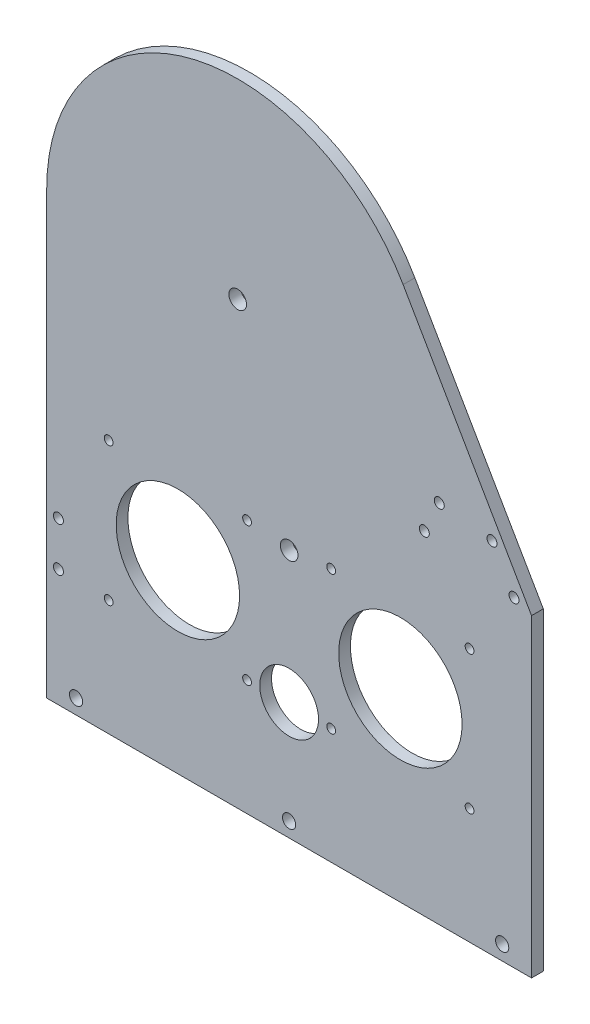
SolidWorks part; units mm, degrees
ref_plane "Plan1" through (0, 0, 0) normal (0, 0, 1) x (1, 0, 0)
ref_plane "Plan2" through (0, 0, 0) normal (0, 1, 0) x (1, 0, 0)
ref_plane "Plan3" through (0, 0, 0) normal (1, 0, 0) x (0, 0, -1)
sketch "Esquisse1" plane through (0, 0, 0) normal (0, 0, 1) x (1, 0, 0)
  line L0 (0, 0) -> (165, 0)
  line L1 (0, 0) -> (0, 150)
  line L2 (165, 0) -> (165, 106.7949)
  line L3 (121.2917, 182.5) -> (165, 106.7949)
  line L4 (65, 230) -> (65, -44.55) construction
  line L5 (82.5, 136.5342) -> (82.5, 70) construction
  line L7 (-20, 5) -> (177.6928, 5) construction
  line L8 (82.5, 55) -> (82.5, -10) construction
  line L9 (115.5875, 84.808) -> (30.4034, 84.808) construction
  line L10 (44.64, 114.9536) -> (44.64, 32.9129) construction
  line L11 (79.1249, 62.958) -> (10, 62.958) construction
  line L12 (120.36, 97.1102) -> (120.36, 28.6591) construction
  line L13 (163.2282, 101.8638) -> (129.7474, 159.8542) construction
  line L14 (178.0627, 114.3329) -> (156.7237, 102.0128) construction
  arc A0 (121.2917, 182.5) -> (0, 150) centre (65, 150) ccw
  circle A1 centre (65, 150) radius 3
  circle A2 centre (82.5, 40) radius 10
  circle A3 centre (82.5, 5) radius 2.25
  circle A4 centre (10, 5) radius 2.25
  circle A5 centre (155, 5) radius 2.25
  circle A6 centre (4, 40) radius 1.7
  circle A7 centre (4, 55) radius 1.7
  circle A8 centre (82.5, 84.808) radius 3
  circle A9 centre (44.64, 62.958) radius 21
  circle A10 centre (120.36, 62.958) radius 21
  circle A19 centre (151.5375, 122.1126) radius 1.7
  circle A20 centre (159.0375, 109.1222) radius 1.7
  circle A21 centre (128.5, 113.5) radius 1.7
  circle A22 centre (133.6, 124.3) radius 1.7
  dimension "D5" = 130
  dimension "D6" = 6
  dimension "D8" = 20
  dimension "D14" = 4.5
  dimension "D18" = 3.4
  dimension "D22" = 3.4
  dimension "D24" = 6
  dimension "D27" = 42
  dimension "D30" = 42
  dimension "D54" = 3.4
  dimension "D55" = 3.4
  dimension "D60" = 3.4
  dimension "D61" = 3.4
  dimension "D7" = 40
  dimension "D1" = 165
  dimension "D2" = 150
  dimension "D3" = 30
  dimension "D4" = 65
  dimension "D9" = 17.5
  dimension "D11" = 5
  dimension "D15" = 72.5
  dimension "D16" = 17.5
  dimension "D17" = 72.5
  dimension "D19" = 40
  dimension "D20" = 4
  dimension "D21" = 15
  dimension "D23" = 4
  dimension "D25" = 67.5
  dimension "D26" = 17.5
  dimension "D28" = 21.85
  dimension "D29" = 37.86
  dimension "D31" = 37.86
  dimension "D32" = 21.85
  dimension "D53" = 4
  dimension "D56" = 15
  dimension "D57" = 5
  dimension "D59" = 87.42
  dimension "D62" = 68.6
  dimension "D63" = 25.7
  dimension "D64" = 63.5
  dimension "D65" = 36.5
extrude "Base-Extrusion" add sketch "Esquisse1" along normal blind 4
sketch "Esquisse2" plane through (0, 0, 4) normal (0, 0, 1) x (1, 0, 0)
  circle A0 centre (21.09, 86.508) radius 1.5
  circle A1 centre (44.64, 62.958) radius 21 construction
  dimension "D1" = 23.55
  dimension "D2" = 23.55
  dimension "D3" = 3
extrude "Enlèv. mat.-Extru.1" cut sketch "Esquisse2" against normal through all
pattern_linear "Répétition linéaire1" count 2 spacing 47.1 count 2 spacing 47.1
sketch "Esquisse3" plane through (31.5489, 23.3651, 4) normal (0, 0, 1) x (1, 0, 0)
  circle A0 centre (65.2611, 63.1429) radius 1.5
  circle A2 centre (88.8111, 39.5929) radius 21 construction
  dimension "D1" = 23.55
  dimension "D2" = 23.55
  dimension "D3" = 3
extrude "Enlèv. mat.-Extru.2" cut sketch "Esquisse3" against normal through all
pattern_linear "Répétition linéaire2" count 2 spacing 47.1 count 2 spacing 47.1
